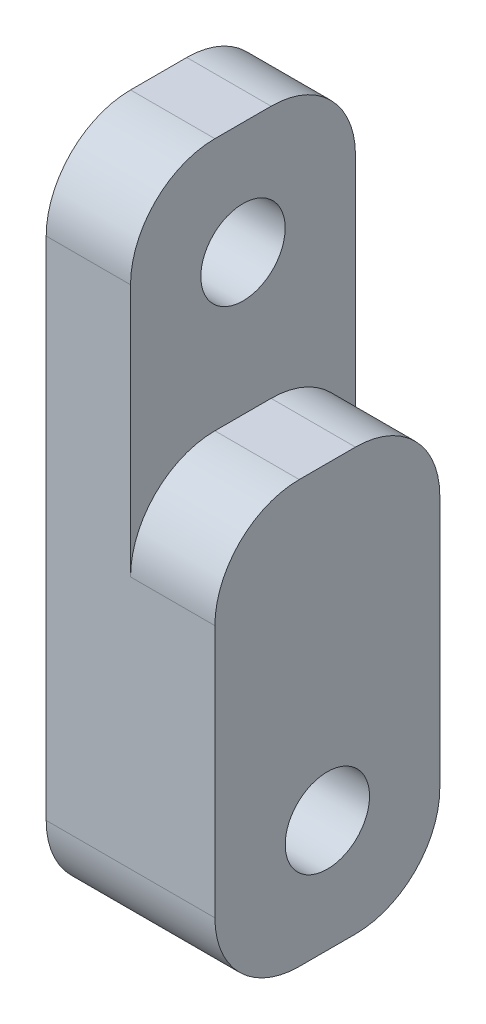
SolidWorks part; units mm, degrees
material "ABS"
ref_plane "Front Plane" through (0, 0, 0) normal (0, 0, 1) x (1, 0, 0)
ref_plane "Top Plane" through (0, 0, 0) normal (0, 1, 0) x (1, 0, 0)
ref_plane "Right Plane" through (0, 0, 0) normal (1, 0, 0) x (0, 0, -1)
sketch "Sketch1" plane through (0, 0, 0) normal (1, 0, 0) x (0, 0, -1)
  line L0 (0, -40) -> (0, 40) construction
  line L2 (-20, 60) -> (20, 60)
  line L3 (-20, 60) -> (-20, -60)
  line L4 (-20, -60) -> (20, -60)
  line L5 (20, 60) -> (20, -60)
  circle A0 centre (0, 40) radius 7.5
  circle A1 centre (0, -40) radius 7.5
  point P3 (0, 0)
  point P10 (20, 0)
  point P11 (0, 60)
  dimension "D1" = 15
  dimension "80" = 80
  dimension "D3" = 120
  dimension "D4" = 40
extrude "Boss-Extrude1" add sketch "Sketch1" along normal blind 30 contours L2 L5 L4 L3
fillet "Fillet1" radius 15 4 edges at (15, -60, -20) (15, -60, 20) (15, 60, -20) (15, 60, 20)
sketch "Sketch2" plane through (30, 0, 0) normal (1, 0, 0) x (0, 0, -1)
  line L0 (-20, 15) -> (20, 15)
  line L2 (20, -45) -> (20, 45)
  line L3 (-20, 45) -> (-20, -45)
  line L4 (20, -45) -> (20, 45)
  line L5 (-20, 45) -> (-20, -45)
  line L9 (-5, -60) -> (5, -60)
  line L10 (-5, -60) -> (5, -60)
  line L11 (5, 60) -> (-5, 60)
  line L12 (5, 60) -> (-5, 60)
  arc A4 (-20, -45) -> (-5, -60) centre (-5, -45) ccw
  arc A5 (5, -60) -> (20, -45) centre (5, -45) ccw
  arc A6 (20, 45) -> (5, 60) centre (5, 45) ccw
  arc A7 (-5, 60) -> (-20, 45) centre (-5, 45) ccw
  arc A8 (-20, -45) -> (-5, -60) centre (-5, -45) ccw
  arc A9 (5, -60) -> (20, -45) centre (5, -45) ccw
  arc A10 (20, 45) -> (5, 60) centre (5, 45) ccw
  arc A11 (-5, 60) -> (-20, 45) centre (-5, 45) ccw
  circle M8 centre (0, 40) radius 7.5
  line M11 (20, -45) -> (20, 45)
  arc M12 (20, 45) -> (5, 60) centre (5, 45) ccw
  arc M13 (-5, 60) -> (-20, 45) centre (-5, 45) ccw
  line M14 (-20, 45) -> (-20, -45)
  dimension "D2" = 30
  dimension "D1" = 0
extrude "Cut-Extrude1" cut sketch "Sketch2" against normal blind 15 contours L0 M14 M11 M12 M13 M8 | A11 L5 A8 A9 L4 A10
fillet "Fillet2" radius 15 2 edges at (22.5, 15, -20) (22.5, 15, 20)
